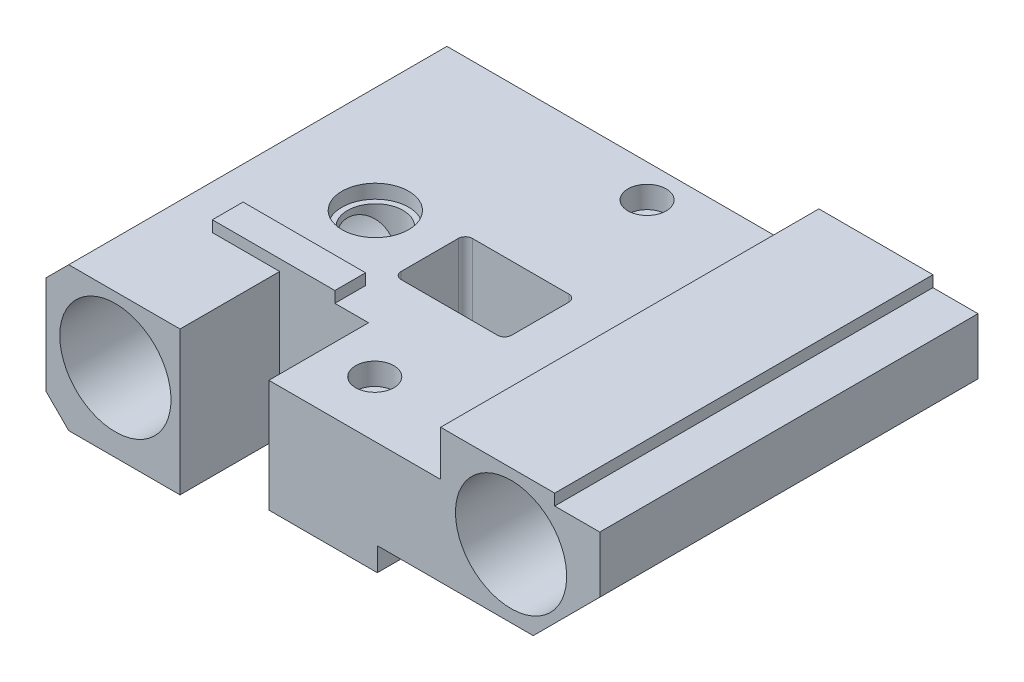
SolidWorks part; units mm, degrees
material "1060 Alloy"
ref_plane "Front Plane" through (0, 0, 0) normal (0, 0, 1) x (1, 0, 0)
ref_plane "Top Plane" through (0, 0, 0) normal (0, 1, 0) x (1, 0, 0)
ref_plane "Right Plane" through (0, 0, 0) normal (1, 0, 0) x (0, 0, -1)
sketch "Sketch1" plane through (0, 0, 0) normal (0, 1, 0) x (1, 0, 0)
  line L1 (0, 0) -> (158.11, 0)
  line L2 (0, 0) -> (0, -108)
  line L3 (0, -108) -> (158.11, -108)
  line L4 (158.11, 0) -> (158.11, -108)
  dimension "D1" = 108
  dimension "D2" = 158.11
extrude "Boss-Extrude1" add sketch "Sketch1" along normal blind 53.94
sketch "Sketch2" plane through (0, 53.94, 0) normal (0, 1, 0) x (-1, 0, 0)
  line L0 (-158.11, 0) -> (0, 0) construction
  line L1 (-158.11, 108) -> (-145.25, 108)
  line L2 (-158.11, 108) -> (-158.11, 0)
  line L3 (-158.11, 0) -> (-145.25, 0)
  line L4 (-145.25, 108) -> (-145.25, 0)
  dimension "D1" = 12.86
extrude "Cut-Extrude1" cut sketch "Sketch2" against normal blind 3.2
sketch "Sketch3" plane through (0, 53.94, 0) normal (0, 1, 0) x (-1, 0, 0)
  line L0 (-145.25, 0) -> (0, 0) construction
  line L1 (0, 108) -> (-112.68, 108)
  line L2 (0, 108) -> (0, 0)
  line L3 (0, 0) -> (-112.68, 0)
  line L4 (-112.68, 108) -> (-112.68, 0)
  dimension "D1" = 112.68
extrude "Cut-Extrude2" cut sketch "Sketch3" against normal blind 12.91
sketch "Sketch4" plane through (0, 0, 0) normal (0, -1, 0) x (1, 0, 0)
  line L0 (158.11, 0) -> (0, 0) construction
  line L1 (158.11, 108) -> (53.39, 108)
  line L2 (158.11, 108) -> (158.11, 0)
  line L3 (158.11, 0) -> (53.39, 0)
  line L4 (53.39, 108) -> (53.39, 0)
  dimension "D1" = 104.72
extrude "Cut-Extrude3" cut sketch "Sketch4" against normal blind 8.92
sketch "Sketch5" plane through (0, 0, 0) normal (0, -1, 0) x (1, 0, 0)
  line L1 (158.11, -6.7843) -> (94.6, -6.7843)
  line L2 (158.11, -6.7843) -> (158.11, 182.4716)
  line L3 (158.11, 182.4716) -> (94.6, 182.4716)
  line L4 (94.6, -6.7843) -> (94.6, 182.4716)
  dimension "D1" = 63.51
extrude "Cut-Extrude4" cut sketch "Sketch5" against normal blind 15.62
sketch "Sketch6" plane through (0, 53.94, 0) normal (0, 1, 0) x (-1, 0, 0)
  line L1 (-63.64, 108) -> (-38.27, 108)
  line L2 (-63.64, 108) -> (-63.64, 79.55)
  line L3 (-63.64, 79.55) -> (-38.27, 79.55)
  line L4 (-38.27, 108) -> (-38.27, 79.55)
  dimension "D1" = 25.37
  dimension "D2" = 28.45
  dimension "D3" = 38.27
extrude "Cut-Extrude5" cut sketch "Sketch6" against normal through all
sketch "Sketch7" plane through (0, 41.03, 0) normal (0, 1, 0) x (1, 0, 0)
  line L1 (55.6, -64.22) -> (87.15, -64.22)
  line L2 (55.6, -64.22) -> (55.6, -43.86)
  line L3 (55.6, -43.86) -> (87.15, -43.86)
  line L4 (87.15, -64.22) -> (87.15, -43.86)
  dimension "D1" = 31.55
  dimension "D2" = 20.36
  dimension "D3" = 43.78
  dimension "D4" = 55.6
extrude "Cut-Extrude6" cut sketch "Sketch7" against normal through all
fillet "Fillet1" radius 2 4 edges at (55.6, 24.975, 43.86) (87.15, 24.975, 43.86) (87.15, 24.975, 64.22) (55.6, 24.975, 64.22)
chamfer "Chamfer1" distance 6.48 angle 45 2 edges at (0, 0, 54) (0, 41.03, 54)
chamfer "Chamfer2" distance 18.99 angle 45 1 edges at (158.11, 15.62, 54)
hole_wizard "Hole1" positions "Sketch9" profile "Sketch8" legacy end condition through all
sketch "Sketch9" plane through (0, 0, 0) normal (0, 0, -1) x (-1, 0, 0)
  line L0 (0, 34.55) -> (0, 6.48) construction
  line L2 (-53.39, 0) -> (-6.48, 0) construction
  line L3 (-145.25, 53.94) -> (-112.68, 53.94) construction
  line L4 (-158.11, 50.74) -> (-158.11, 34.61) construction
  point P0 (-19.812, 22.225)
  point P1 (-132.7862, 35.017)
  dimension "D1" = 19.812
  dimension "D2" = 22.225
  dimension "D3" = 18.923
  dimension "D4" = 25.3238
sketch "Sketch8" plane through (19.812, 22.225, 0) normal (1, 0, 0) x (0, 1, 0)
  line L0 (0, 0) -> (0, 108)
  line L1 (0, 108) -> (15.875, 108)
  line L2 (15.875, 108) -> (15.875, 0)
  line L3 (15.875, 0) -> (0, 0)
  line L4 (0, 110) -> (0, -10) construction
  dimension "Diameter" = 31.75
  dimension "Depth" = 108
sketch "Sketch10" plane through (0, 8.92, 0) normal (0, -1, 0) x (1, 0, 0)
  line L0 (85.15, 43.86) -> (57.6, 43.86) construction
  line L1 (63.804, 43.86) -> (83.235, 43.86)
  line L2 (63.804, 43.86) -> (63.804, 0)
  line L3 (63.804, 0) -> (83.235, 0)
  line L4 (83.235, 43.86) -> (83.235, 0)
  line L5 (53.39, 0) -> (94.6, 0) construction
  dimension "D1" = 19.431
  dimension "D2" = 10.414
extrude "Cut-Extrude7" cut sketch "Sketch10" against normal blind 6.223
sketch "Sketch11" plane through (0, 0, 0) normal (0, -1, 0) x (1, 0, 0)
  line L0 (53.39, 0) -> (6.48, 0) construction
  line L1 (0, 0) -> (0, 108) construction
  circle A0 centre (36.83, 50.8) radius 9.525
  dimension "D3" = 19.05
  dimension "D1" = 50.8
  dimension "D2" = 36.83
extrude "Cut-Extrude10" cut sketch "Sketch11" against normal blind 6.6802
sketch "Sketch12" plane through (0, 6.6802, 0) normal (0, -1, 0) x (1, 0, 0)
  line L0 (0, 0) -> (0, 108) construction
  line L1 (53.39, 0) -> (6.48, 0) construction
  circle A0 centre (36.83, 50.8) radius 7.9375
  dimension "D1" = 36.83
  dimension "D2" = 50.8
extrude "Cut-Extrude11" cut sketch "Sketch12" against normal through all
sketch "Sketch13" plane through (0, 41.03, 0) normal (0, 1, 0) x (-1, 0, 0)
  line L0 (0, 108) -> (0, 0) construction
  line L1 (-112.68, 0) -> (-6.48, 0) construction
  circle A0 centre (-36.83, 50.8) radius 9.525
  dimension "D1" = 36.83
  dimension "D2" = 50.8
extrude "Cut-Extrude12" cut sketch "Sketch13" against normal blind 3.9624
sketch "Sketch14" plane through (0, 41.03, 0) normal (0, 1, 0) x (1, 0, 0)
  line L0 (38.27, -79.55) -> (63.64, -79.55) construction
  line L1 (54.0258, -79.55) -> (19.05, -79.55)
  line L2 (54.0258, -79.55) -> (54.0258, -70.787)
  line L3 (54.0258, -70.787) -> (19.05, -70.787)
  line L4 (19.05, -79.55) -> (19.05, -70.787)
  line L5 (0, -108) -> (0, 0) construction
  dimension "D1" = 34.9758
  dimension "D2" = 19.05
  dimension "D3" = 8.763
extrude "Boss-Extrude2" add sketch "Sketch14" along normal blind 3.175
hole_wizard "Hole2" positions "Sketch16" profile "Sketch17" legacy end condition through all
sketch "Sketch16" plane through (0, 41.03, 0) normal (0, 1, 0) x (-1, 0, 0)
  line L0 (-63.64, 108) -> (-112.68, 108) construction
  line L1 (-63.64, 79.55) -> (-63.64, 108) construction
  line L2 (-112.68, 0) -> (-6.48, 0) construction
  line L3 (0, 108) -> (0, 0) construction
  point P0 (-73.025, 9.398)
  point P1 (-77.864, 91.998)
  dimension "D1" = 16.002
  dimension "D2" = 14.224
  dimension "D3" = 9.398
  dimension "D4" = 73.025
sketch "Sketch17" plane through (73.025, 41.03, 9.398) normal (1, 0, 0) x (0, 0, 1)
  line L0 (0, 0) -> (0, 41.03)
  line L1 (0, 41.03) -> (2.8893, 41.03)
  line L2 (2.8893, 41.03) -> (2.8893, 6.2738)
  line L3 (2.8893, 6.2738) -> (5.461, 6.2738)
  line L4 (5.461, 6.2738) -> (5.461, 0)
  line L5 (5.461, 0) -> (0, 0)
  line L6 (0, 110) -> (0, -10) construction
  dimension "Diameter" = 5.7785
  dimension "Depth" = 41.03
  dimension "C-Bore Diameter" = 10.922
  dimension "C-Bore Depth" = 6.2738
sketch "Sketch18" plane through (0, 8.92, 0) normal (0, -1, 0) x (1, 0, 0)
  circle A0 centre (77.864, 91.998) radius 7.9375
extrude "Cut-Extrude13" cut sketch "Sketch18" against normal blind 6.35
hole_wizard "Hole3" positions "Sketch20" profile "Sketch19" legacy end condition through all
sketch "Sketch20" plane through (0, 41.03, 0) normal (0, 1, 0) x (-1, 0, 0)
  line L0 (-112.68, 0) -> (-6.48, 0) construction
  line L1 (-158.11, 108) -> (-158.11, 0) construction
  point P0 (-107.2084, 44.5262)
  point P1 (-107.2084, 63.5762)
  dimension "D1" = 19.05
  dimension "D2" = 44.5262
  dimension "D3" = 50.9016
sketch "Sketch19" plane through (107.2084, 41.03, 44.5262) normal (1, 0, 0) x (0, 0, 1)
  line L0 (0, 0) -> (0, 41.03)
  line L1 (0, 41.03) -> (2.667, 41.03)
  line L2 (2.667, 41.03) -> (2.667, 5.334)
  line L3 (2.667, 5.334) -> (4.5212, 5.334)
  line L4 (4.5212, 5.334) -> (4.5212, 0)
  line L5 (4.5212, 0) -> (0, 0)
  line L6 (0, 110) -> (0, -10) construction
  dimension "Diameter" = 5.334
  dimension "Depth" = 41.03
  dimension "C-Bore Diameter" = 9.0424
  dimension "C-Bore Depth" = 5.334
